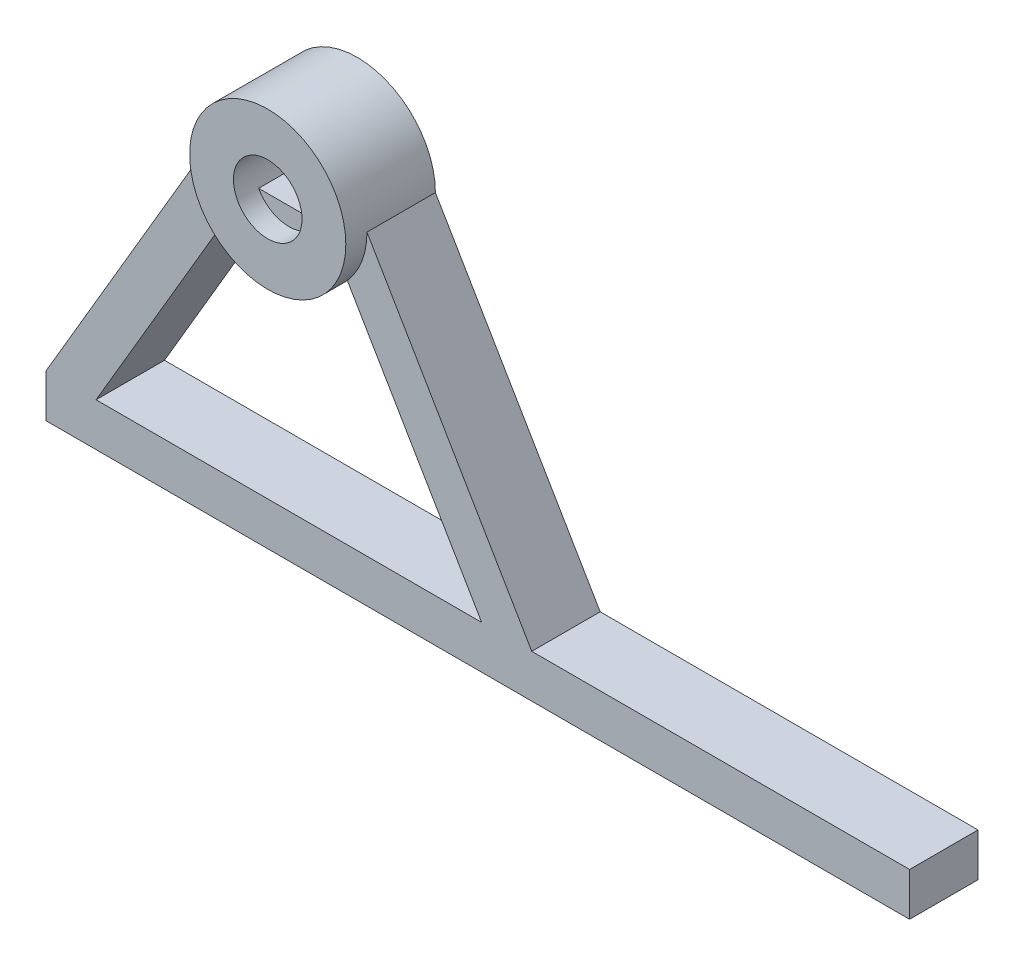
SolidWorks part; units mm, degrees
ref_plane "Front Plane" through (0, 0, 0) normal (0, 0, 1) x (1, 0, 0)
ref_plane "Top Plane" through (0, 0, 0) normal (0, 1, 0) x (1, 0, 0)
ref_plane "Right Plane" through (0, 0, 0) normal (1, 0, 0) x (0, 0, -1)
sketch "Sketch1" plane through (0, 0, 0) normal (0, 0, 1) x (1, 0, 0)
  line L0 (-22.5, -17.68) -> (-7.2357, 8.32)
  line L1 (-22.5, -21.68) -> (22.5, -21.68)
  line L2 (-22.5, -21.68) -> (-22.5, -17.68)
  line L4 (22.5, -21.68) -> (22.5, -17.68)
  line L5 (22.5, -17.68) -> (7.2357, 8.32)
  line L6 (-2.7983, 9.82) -> (2.7983, 9.82)
  line L7 (-2.7983, 6.82) -> (2.7983, 6.82)
  line L8 (17.8616, -17.68) -> (3.1138, 7.4402)
  line L9 (-17.8616, -17.68) -> (-3.1138, 7.4402)
  line L10 (-17.8616, -17.68) -> (-17.8616, -17.68)
  line L11 (-17.8616, -17.68) -> (17.8616, -17.68)
  line L12 (17.8616, -17.68) -> (17.8616, -17.68)
  circle A1 centre (0, 8.32) radius 3.175
  arc A2 (3.1138, 7.4402) -> (-3.1138, 7.4402) centre (0, 8.32) ccw
  circle A3 centre (0, 8.32) radius 7.2357
  arc A4 (7.2357, 8.32) -> (-7.2357, 8.32) centre (0, 8.32) ccw construction
  point P21 (0, -21.68)
  point P24 (0, -17.68)
  dimension "D1" = 6.35
  dimension "D8" = 14.4714
  dimension "D2" = 1.5
  dimension "D3" = 1.5
  dimension "D4" = 4
  dimension "D5" = 4
  dimension "D6" = 30
  dimension "D7" = 45
  dimension "D9" = 8.32
extrude "Boss-Extrude1" add sketch "Sketch1" along normal blind 6.34 contours L6 A1 | L7 A1 | A3 L9 A2 L8 | A3 L0 L2 L1 L4 L5 L8 L11 L9 | L9 A3 L8 A2 A1
ref_plane "Plane1" through (0, 14.32, 0) normal (0, 1, 0) x (1, 0, 0)
sketch "Sketch2" [suppressed] plane through (0, 14.32, 0) normal (0, 1, 0) x (1, 0, 0)
  line L0 (7.2357, 0) -> (-7.2357, 0) construction
  circle A0 centre (0, -3.17) radius 1.6
  dimension "D1" = 3.2
  dimension "D2" = 3.17
sketch "Sketch3" plane through (0, 0, 0) normal (0, 0, -1) x (-1, 0, 0)
  arc A0 (7.2357, 8.32) -> (-7.2357, 8.32) centre (0, 8.32) ccw construction
  arc A1 (-2.7983, 9.82) -> (-2.7983, 6.82) centre (0, 8.32) ccw construction
  arc A2 (7.2357, 8.32) -> (-7.2357, 8.32) centre (0, 8.32) ccw construction
  arc A3 (-2.7983, 9.82) -> (-2.7983, 6.82) centre (0, 8.32) ccw construction
  circle A4 centre (0, 8.32) radius 7.2357
sketch "Sketch5" plane through (0, 0, 6.34) normal (0, 0, 1) x (1, 0, 0)
  line L0 (22.5, -21.68) -> (22.5, -17.68) construction
  line L1 (-22.5, -21.68) -> (-22.5, -17.68) construction
  line L2 (-22.5, -21.68) -> (22.5, -21.68) construction
  line L3 (-17.8616, -17.68) -> (17.8616, -17.68) construction
  line L4 (22.5, -21.68) -> (22.5, -17.68) construction
  line L5 (-22.5, -21.68) -> (-22.5, -17.68) construction
  line L6 (-22.5, -21.68) -> (22.5, -21.68) construction
  line L7 (-17.8616, -17.68) -> (17.8616, -17.68) construction
  line L9 (-22.5, -21.68) -> (22.5, -21.68)
  line L10 (-22.5, -21.68) -> (-22.5, -17.68)
  line L11 (-22.5, -17.68) -> (22.5, -17.68)
  line L12 (22.5, -21.68) -> (22.5, -17.68)
sketch "Sketch6" plane through (0, 0, 6.34) normal (0, 0, 1) x (1, 0, 0)
  circle A0 centre (0, 8.32) radius 7.2357 construction
  circle A1 centre (0, 8.32) radius 7.2357
  circle A2 centre (0, 8.32) radius 3.175
extrude "Boss-Extrude2" add sketch "Sketch6" along normal blind 1.96
sketch "Sketch7" plane through (-22.5, 0, 0) normal (-1, 0, 0) x (0, 0, 1)
  line L4 (0, -17.68) -> (0, -21.68)
  line L5 (0, -21.68) -> (6.34, -21.68)
  line L6 (6.34, -21.68) -> (6.34, -17.68)
  line L7 (6.34, -17.68) -> (0, -17.68)
  line L8 (0, -17.68) -> (0, -21.68)
  line L9 (0, -21.68) -> (6.34, -21.68)
  line L10 (6.34, -21.68) -> (6.34, -17.68)
  line L11 (6.34, -17.68) -> (0, -17.68)
  dimension "D1" = 0
sketch "Sketch8" plane through (22.5, 0, 0) normal (1, 0, 0) x (0, 0, -1)
  line L4 (0, -21.68) -> (0, -17.68)
  line L5 (0, -17.68) -> (-6.34, -17.68)
  line L6 (-6.34, -17.68) -> (-6.34, -21.68)
  line L7 (-6.34, -21.68) -> (0, -21.68)
  line L8 (0, -21.68) -> (0, -17.68)
  line L9 (0, -17.68) -> (-6.34, -17.68)
  line L10 (-6.34, -17.68) -> (-6.34, -21.68)
  line L11 (-6.34, -21.68) -> (0, -21.68)
  dimension "D1" = 0
extrude "Boss-Extrude4" add sketch "Sketch8" along normal blind 35
